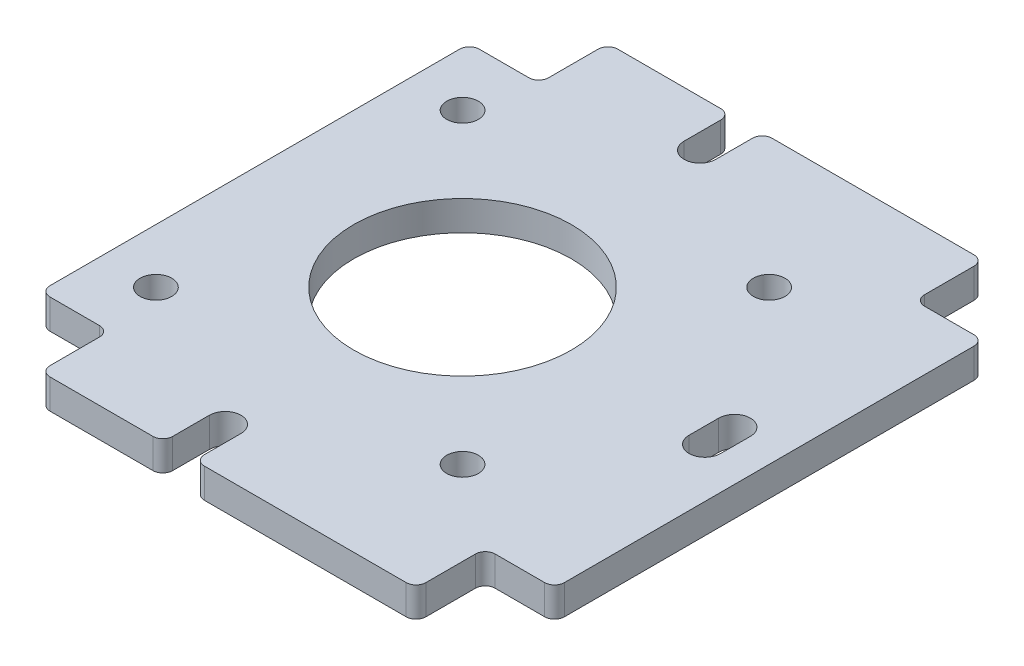
SolidWorks part; units mm, degrees
material "AISI 1045 Steel, cold drawn"
ref_plane "Front Plane" through (0, 0, 0) normal (0, 0, 1) x (1, 0, 0)
ref_plane "Top Plane" through (0, 0, 0) normal (0, 1, 0) x (1, 0, 0)
ref_plane "Right Plane" through (0, 0, 0) normal (1, 0, 0) x (0, 0, -1)
sketch "Sketch1" plane through (0, 0, 0) normal (0, 1, 0) x (1, 0, 0)
  line L1 (15.5, -15.5) -> (-15.5, -15.5) construction
  line L2 (15.5, -15.5) -> (15.5, 15.5) construction
  line L3 (15.5, 15.5) -> (-15.5, 15.5) construction
  line L4 (-15.5, -15.5) -> (-15.5, 15.5) construction
  line L5 (15.5, -15.5) -> (-15.5, 15.5) construction
  line L6 (15.5, 15.5) -> (-15.5, -15.5) construction
  line L7 (21, -21) -> (-21, -21)
  line L8 (21, -21) -> (21, 21)
  line L9 (21, 21) -> (-21, 21)
  line L10 (-21, -21) -> (-21, 21)
  line L11 (21, -21) -> (-21, 21) construction
  line L12 (21, 21) -> (-21, -21) construction
  circle A0 centre (0, 0) radius 11
  dimension "D1" = 22
  dimension "D2" = 31
  dimension "D3" = 42
extrude "Boss-Extrude1" add sketch "Sketch1" along normal mid plane 3
hole_wizard "M3 Clearance Hole1" positions "Sketch2" profile "Sketch3" hole size "M3" standard "ANSI Metric" end condition through all
sketch "Sketch2" plane through (0, 1.5, 0) normal (0, 1, 0) x (1, 0, 0)
  point P0 (-15.5, 15.5)
  point P3 (15.5, 15.5)
  point P6 (15.5, -15.5)
  point P9 (-15.5, -15.5)
sketch "Sketch3" plane through (-15.5, 1.5, -15.5) normal (1, 0, 0) x (0, 0, 1)
  line L0 (0, 0) -> (0, 3)
  line L1 (0, 3) -> (1.6, 3)
  line L2 (1.6, 3) -> (1.6, 0)
  line L5 (1.6, 0) -> (0, 0)
  line L11 (0, -6.35) -> (0, 107.95) construction
  dimension "Thru Hole Dia." = 3.2
  dimension "Thru Hole Depth" = 3
sketch "Sketch4" plane through (0, 1.5, 0) normal (0, 1, 0) x (1, 0, 0)
  line L0 (0, -24) -> (0, -29) construction
  line L1 (1.6, -24) -> (1.6, -28.7)
  line L2 (-1.6, -24) -> (-1.6, -28.7)
  line L3 (26, 1.5) -> (26, -1.5) construction
  line L4 (27.6, 1.5) -> (27.6, -1.5)
  line L5 (24.4, 1.5) -> (24.4, -1.5)
  line L6 (-14, -21) -> (14, -21)
  line L9 (-21, -21) -> (21, -21) construction
  line L11 (21, -21) -> (21, 21) construction
  line L12 (21, 0) -> (-21, 0) construction
  line L13 (0, 24) -> (0, 29) construction
  line L14 (1.6, 28.7) -> (14, 28.7)
  line L15 (-14, -21) -> (-14, -28.7)
  line L16 (-14, -28.7) -> (-1.6, -28.7)
  line L17 (14, -28.7) -> (14, -21)
  line L18 (-21, 21) -> (-21, -21) construction
  line L19 (1.6, -28.7) -> (14, -28.7)
  line L20 (14, 28.7) -> (14, 21)
  line L21 (-14, 28.7) -> (-1.6, 28.7)
  line L22 (-14, 21) -> (-14, 28.7)
  line L23 (-14, 21) -> (14, 21)
  line L24 (-1.6, 24) -> (-1.6, 28.7)
  line L25 (1.6, 24) -> (1.6, 28.7)
  line L26 (21, 14) -> (31, 14)
  line L27 (31, 14) -> (31, -14)
  line L28 (31, -14) -> (21, -14)
  line L29 (21, 21) -> (-21, 21) construction
  line L30 (21, 14) -> (21, -14)
  arc A0 (1.6, -24) -> (-1.6, -24) centre (0, -24) ccw
  arc A2 (27.6, 1.5) -> (24.4, 1.5) centre (26, 1.5) ccw
  arc A3 (24.4, -1.5) -> (27.6, -1.5) centre (26, -1.5) ccw
  arc A6 (1.6, 24) -> (-1.6, 24) centre (0, 24) cw
  point P10 (26, 0)
  point P17 (0, 0)
  dimension "D1" = 1.6
  dimension "D12" = 1.6
  dimension "D2" = 3
  dimension "D3" = 5
  dimension "D4" = 10
  dimension "D5" = 5
  dimension "D6" = 7.7
  dimension "D7" = 7
  dimension "D8" = 7
  dimension "D9" = 7
  dimension "D10" = 7
  dimension "D11" = 3
extrude "Boss-Extrude2" add sketch "Sketch4" against normal up to vertex (3 mm away) up to point (21, -1.5, -21)
sketch "Sketch5" plane through (0, 1.5, 0) normal (0, 1, 0) x (1, 0, 0)
  line L0 (21, -14) -> (31, -14) construction
  line L17 (31, 14) -> (21, 14)
  line L18 (31, 14) -> (31, 21)
  line L19 (31, 21) -> (21, 21)
  line L20 (21, 14) -> (21, 21)
  line L21 (14, 28.7) -> (24, 28.7)
  line L22 (14, 28.7) -> (14, 21)
  line L23 (14, 21) -> (24, 21)
  line L24 (24, 28.7) -> (24, 21)
  line L25 (31, -14) -> (21, -14)
  line L26 (31, -14) -> (31, -21)
  line L27 (31, -21) -> (21, -21)
  line L28 (21, -14) -> (21, -21)
  line L29 (31, -14) -> (31, 14) construction
  line L30 (-14, -21) -> (-14, -28.7) construction
  line L31 (14, -28.7) -> (24, -28.7)
  line L32 (14, -28.7) -> (14, -21)
  line L33 (14, -21) -> (24, -21)
  line L34 (24, -28.7) -> (24, -21)
  line L35 (-21, -21) -> (-14, -21)
  line L36 (-21, -21) -> (-21, -21.7)
  line L37 (-21, -21.7) -> (-14, -21.7)
  line L38 (-14, -21) -> (-14, -21.7)
  line L39 (-14, 28.7) -> (-14, 21) construction
  line L40 (-21, 21) -> (-14, 21)
  line L41 (-21, 21) -> (-21, 21.7)
  line L42 (-21, 21.7) -> (-14, 21.7)
  line L43 (-14, 21) -> (-14, 21.7)
  line L44 (-1.6, 28.7) -> (-14, 28.7) construction
  line L45 (31, 21) -> (24, 21)
  line L46 (31, 21) -> (31, 21.7)
  line L47 (31, 21.7) -> (24, 21.7)
  line L48 (24, 21) -> (24, 21.7)
  line L49 (31, -21) -> (24, -21)
  line L50 (31, -21) -> (31, -21.7)
  line L51 (31, -21.7) -> (24, -21.7)
  line L52 (24, -21) -> (24, -21.7)
  line L53 (-14, -28.7) -> (-1.6, -28.7) construction
  dimension "D1" = 7
  dimension "D2" = 7
  dimension "D3" = 7
extrude "Boss-Extrude3" add sketch "Sketch5" against normal up to surface (3 mm away)
fillet "Fillet1" radius 1 16 edges at (-1.6, 0, 28.7) (1.6, 0, 28.7) (-14, 0, 28.7) (1.6, 0, -28.7) (-1.6, 0, -28.7) (-14, 0, -28.7) (24, 0, -28.7) (24, 0, 28.7) (-21, 0, 21.7) (-14, 0, 21.7) (24, 0, 21.7) (31, 0, 21.7) (31, 0, -21.7) (24, 0, -21.7) (-14, 0, -21.7) (-21, 0, -21.7)
